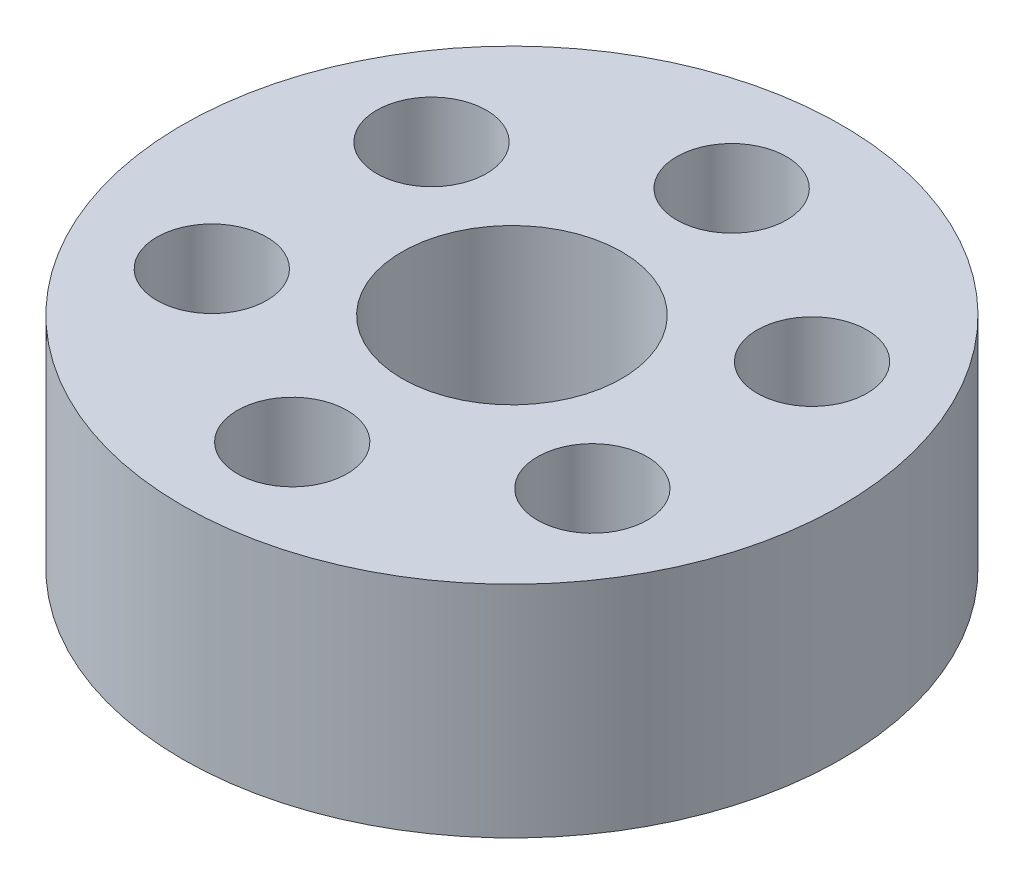
SolidWorks part; units mm, degrees
material "1060 Alloy"
ref_plane "Front Plane" through (0, 0, 0) normal (0, 0, 1) x (1, 0, 0)
ref_plane "Top Plane" through (0, 0, 0) normal (0, 1, 0) x (1, 0, 0)
ref_plane "Right Plane" through (0, 0, 0) normal (1, 0, 0) x (0, 0, -1)
sketch "Sketch1" plane through (0, 0, 0) normal (0, 1, 0) x (1, 0, 0)
  circle A0 centre (0, 0) radius 15
  dimension "D1" = 30
extrude "Boss-Extrude1" add sketch "Sketch1" along normal blind 10
sketch "Sketch2" plane through (0, 10, 0) normal (0, 1, 0) x (1, 0, 0)
  circle A0 centre (0, 0) radius 5
  dimension "D1" = 10
extrude "Cut-Extrude1" cut sketch "Sketch2" against normal through all
sketch "Sketch3" plane through (0, 10, 0) normal (0, 1, 0) x (1, 0, 0)
  circle A1 centre (0, 10) radius 2.5
  circle A2 centre (0, 0) radius 10
  circle A3 centre (0, 0) radius 10 construction
  dimension "D2" = 5
  dimension "D1" = 5
extrude "Cut-Extrude2" cut sketch "Sketch3" against normal through all
pattern_circular "CirPattern1" count 6 over 360 about axis through (0, 0, 0) along (0, 1, 0) of "Cut-Extrude2"
